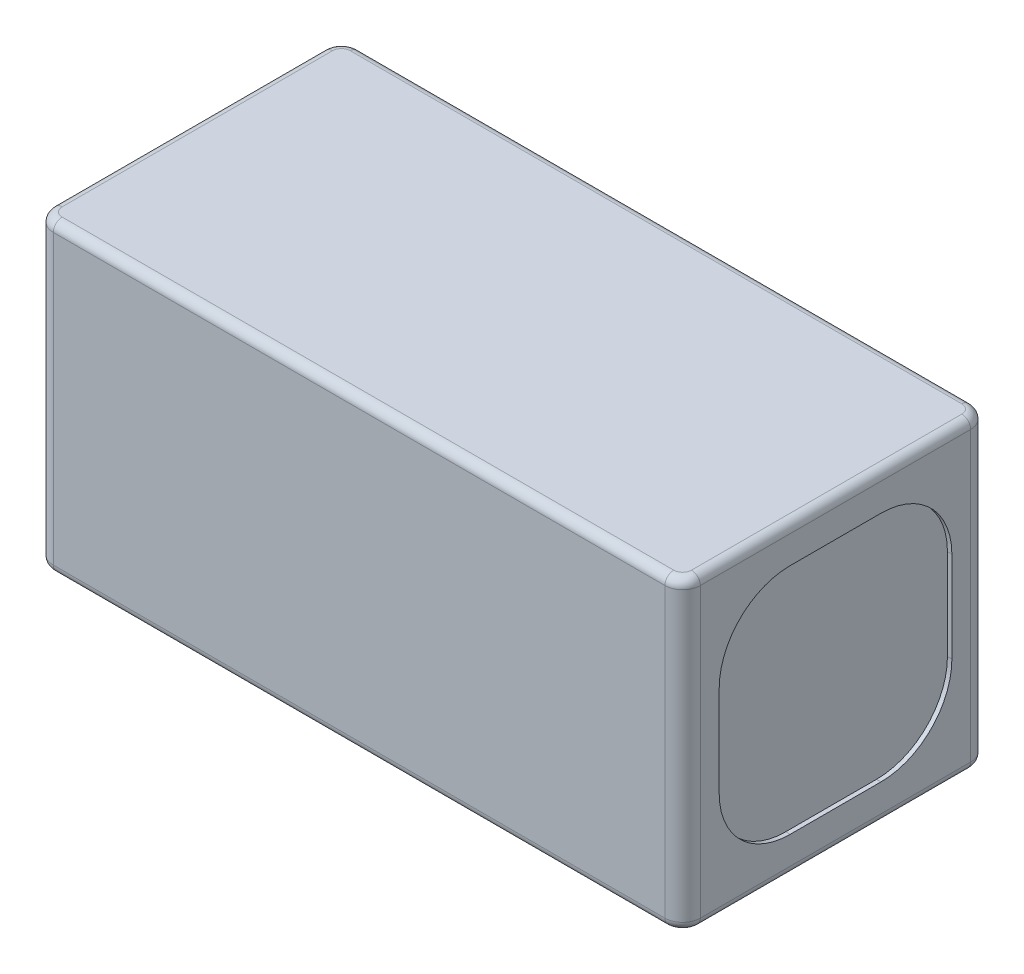
SolidWorks part; units mm, degrees
ref_plane "Front Plane" through (0, 0, 0) normal (0, 0, 1) x (1, 0, 0)
ref_plane "Top Plane" through (0, 0, 0) normal (0, 1, 0) x (1, 0, 0)
ref_plane "Right Plane" through (0, 0, 0) normal (1, 0, 0) x (0, 0, -1)
ref_plane "Plane1" through (0, 0, -15) normal (0, 0, -1) x (-1, 0, 0)
sketch "Sketch1" plane through (0, 0, -15) normal (0, 0, -1) x (-1, 0, 0)
  line L0 (-69, -22) -> (4, -22)
  line L1 (4, -22) -> (4, 12.5)
  line L2 (4, 12.5) -> (-69, 12.5)
  line L3 (-69, 12.5) -> (-69, -22)
  line L4 (-69, -4.75) -> (4, -4.75) construction
  line L5 (-32.5, 12.5) -> (-32.5, -22) construction
  dimension "D1" = 34.5
  dimension "D2" = 73
extrude "Boss-Extrude1" add sketch "Sketch1" against normal blind 34.5
sketch "Sketch2" plane through (69, 0, 0) normal (1, 0, 0) x (0, 0, -1)
  line L0 (-15.375, 0.375) -> (-15.375, -9.875)
  line L1 (-7.375, -17.875) -> (2.875, -17.875)
  line L2 (10.875, -9.875) -> (10.875, 0.375)
  line L3 (2.875, 8.375) -> (-7.375, 8.375)
  line L4 (-19.5, 12.5) -> (15, -22) construction
  line L5 (15, 12.5) -> (-19.5, -22) construction
  line L6 (-15.375, 8.375) -> (10.875, -17.875) construction
  line L7 (10.875, 8.375) -> (-15.375, -17.875) construction
  line L12 (-19.5, 12.5) -> (15, 12.5) construction
  line L13 (-19.5, 12.5) -> (-19.5, -22) construction
  line L14 (-19.5, -22) -> (15, -22) construction
  line L15 (15, 12.5) -> (15, -22) construction
  line L16 (-19.5, 12.5) -> (15, -22) construction
  line L17 (-19.5, -22) -> (15, 12.5) construction
  arc A0 (-15.375, -9.875) -> (-7.375, -17.875) centre (-7.375, -9.875) ccw
  arc A1 (2.875, -17.875) -> (10.875, -9.875) centre (2.875, -9.875) ccw
  arc A2 (10.875, 0.375) -> (2.875, 8.375) centre (2.875, 0.375) ccw
  arc A3 (-15.375, 0.375) -> (-7.375, 8.375) centre (-7.375, 0.375) cw
  point P16 (-2.25, -4.75)
  dimension "D3" = 8
  dimension "D1" = 26.25
  dimension "D2" = 34.5
extrude "Cut-Extrude1" cut sketch "Sketch2" against normal blind 0.5
sketch "Sketch3" plane through (-4, 0, 0) normal (-1, 0, 0) x (0, 0, 1)
  line L0 (7.375, 8.375) -> (-2.875, 8.375)
  line L1 (-10.875, 0.375) -> (-10.875, -9.875)
  line L2 (-2.875, -17.875) -> (7.375, -17.875)
  line L3 (15.375, -9.875) -> (15.375, 0.375)
  line L4 (-10.875, 8.375) -> (15.375, -17.875) construction
  line L5 (15.375, 8.375) -> (-10.875, -17.875) construction
  line L6 (-15, 12.5) -> (19.5, -22) construction
  line L7 (19.5, -22) -> (-15, -22) construction
  line L8 (-15, -22) -> (19.5, 12.5) construction
  arc A0 (-10.875, -9.875) -> (-2.875, -17.875) centre (-2.875, -9.875) ccw
  arc A1 (7.375, -17.875) -> (15.375, -9.875) centre (7.375, -9.875) ccw
  arc A2 (7.375, 8.375) -> (15.375, 0.375) centre (7.375, 0.375) cw
  arc A3 (-2.875, 8.375) -> (-10.875, 0.375) centre (-2.875, 0.375) ccw
  dimension "D3" = 8
  dimension "D1" = 26.25
  dimension "D2" = 34.5
extrude "Cut-Extrude2" cut sketch "Sketch3" against normal blind 0.5
fillet "Fillet1" radius 2 4 edges at (-4, -4.75, -15) (-4, -4.75, 19.5) (69, -4.75, -15) (69, -4.75, 19.5)
fillet "Fillet2" radius 1 16 edges at (68.4142, 12.5, -14.4142) (69, 12.5, 2.25) (32.5, 12.5, -15) (68.4142, 12.5, 18.9142) (-3.4142, 12.5, -14.4142) (32.5, 12.5, 19.5) (-4, 12.5, 2.25) (-3.4142, 12.5, 18.9142) (-4, -22, 2.25) (-3.4142, -22, -14.4142) (-3.4142, -22, 18.9142) (32.5, -22, -15) (32.5, -22, 19.5) (68.4142, -22, -14.4142) (68.4142, -22, 18.9142) (69, -22, 2.25)
sketch "Sketch4" [suppressed] plane through (0, 0, 14) normal (0, 0, 1) x (1, 0, 0)
  line L0 (-102, 2.5) -> (67, 2.5) construction
  line L1 (-102, 26) -> (-102, -21) construction
  line L2 (67, -21) -> (67, 26) construction
  line L3 (-17.5, 25.9735) -> (-17.5, -21) construction
  line L4 (-102, -21) -> (67, -21) construction
  circle A0 centre (-17.5, 2.5) radius 0.5026
equation "\"D1@Sketch3\"=\"D2@Sketch3\" * .75"
equation "\"D1@Sketch2\"=\"D2@Sketch2\"* .75"
